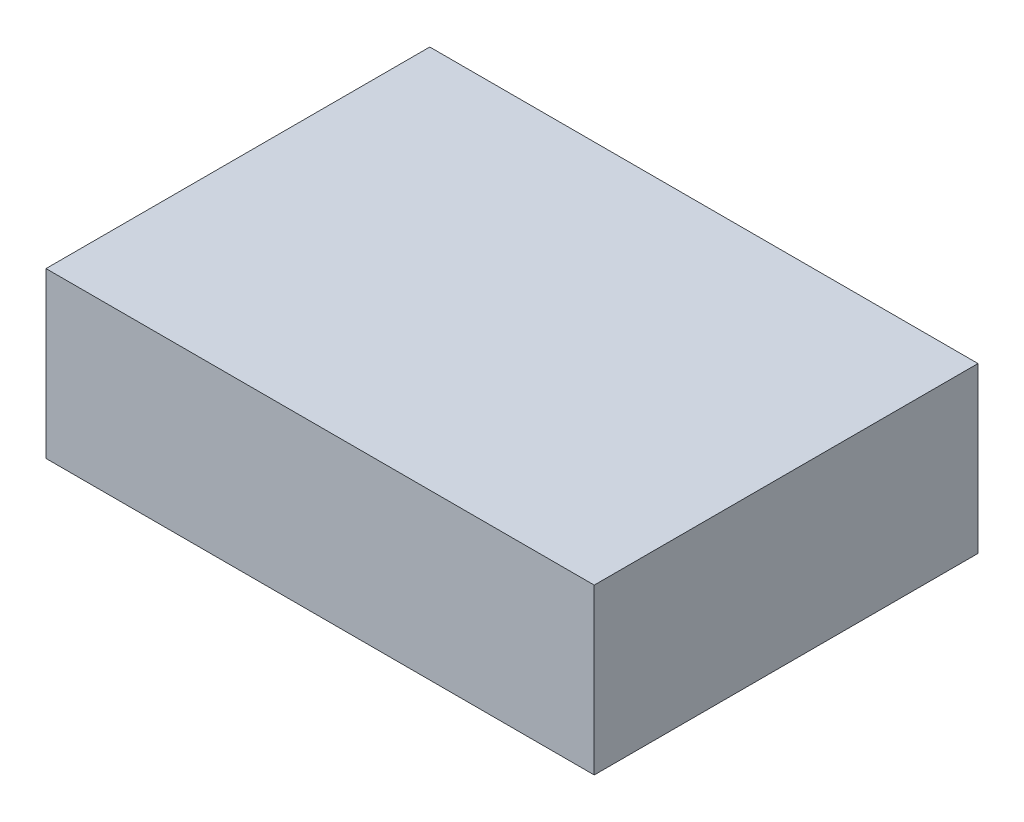
SolidWorks part; units mm, degrees
material "PETG"
ref_plane "Front Plane" through (0, 0, 0) normal (0, 0, 1) x (1, 0, 0)
ref_plane "Top Plane" through (0, 0, 0) normal (0, 1, 0) x (1, 0, 0)
ref_plane "Right Plane" through (0, 0, 0) normal (1, 0, 0) x (0, 0, -1)
sketch "Sketch1" plane through (0, 0, 0) normal (0, 1, 0) x (1, 0, 0)
  line L1 (-56.2982, 44.7529) -> (43.7018, 44.7529)
  line L2 (-56.2982, 44.7529) -> (-56.2982, -25.2471)
  line L3 (-56.2982, -25.2471) -> (43.7018, -25.2471)
  line L4 (43.7018, 44.7529) -> (43.7018, -25.2471)
extrude "Boss-Extrude1" add sketch "Sketch1" along normal blind 30 contours L1 L4 L3 L2
